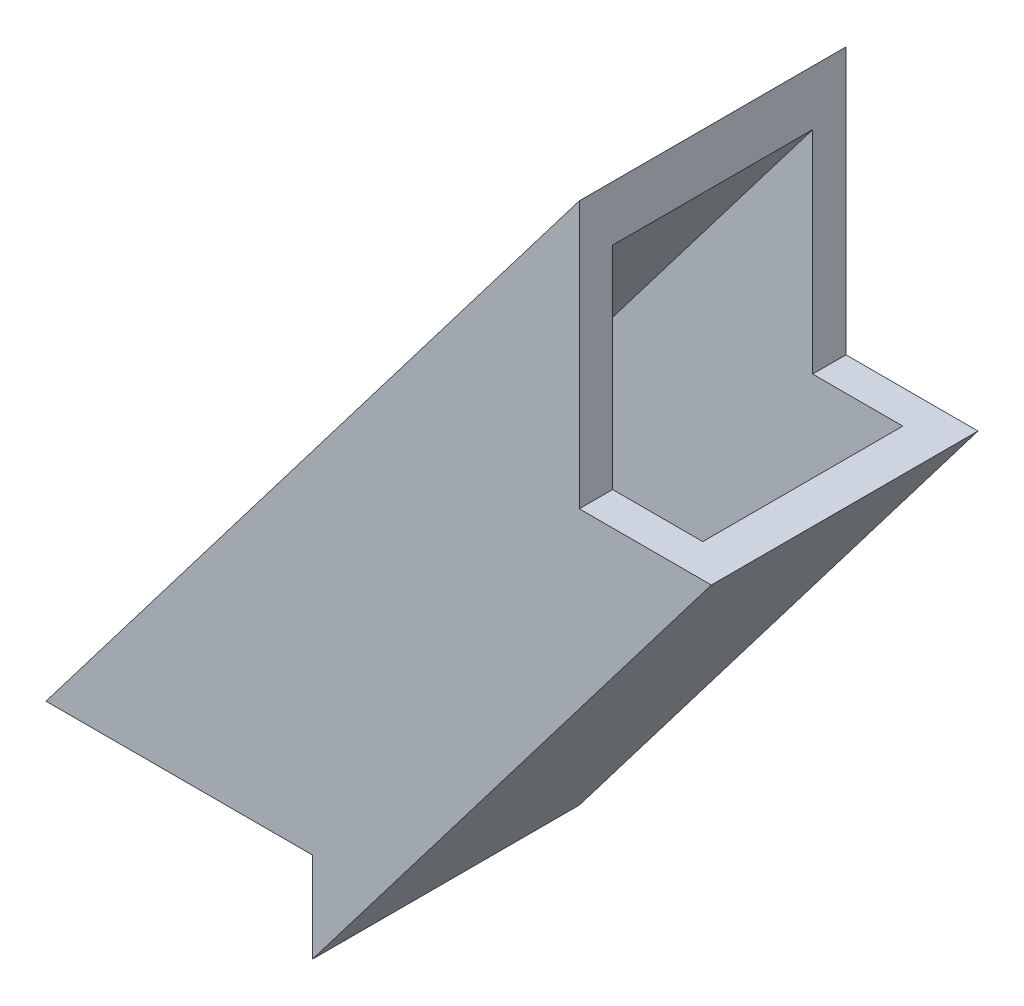
SolidWorks part; units mm, degrees
material "6061-T6 (SS)"
ref_plane "Front Plane" through (0, 0, 0) normal (0, 0, 1) x (1, 0, 0)
ref_plane "Top Plane" through (0, 0, 0) normal (0, 1, 0) x (1, 0, 0)
ref_plane "Right Plane" through (0, 0, 0) normal (1, 0, 0) x (0, 0, -1)
ref_plane "Plane1" through (115.3963, 151.4577, 0) normal (-0.606, -0.7954, 0) x (-0.7954, 0.606, 0)
sketch "Sketch1" plane through (115.3963, 151.4577, 0) normal (-0.606, -0.7954, 0) x (-0.7954, 0.606, 0)
  line L0 (15.3935, -228.6) -> (15.3935, -203.2) construction
  line L1 (-222.1481, -203.2) -> (-196.7481, -203.2)
  line L2 (-222.1481, -203.2) -> (-222.1481, -228.6)
  line L3 (-222.1481, -228.6) -> (-196.7481, -228.6)
  line L4 (-196.7481, -203.2) -> (-196.7481, -228.6)
  line L5 (-222.1481, -203.2) -> (-196.7481, -228.6) construction
  line L6 (-222.1481, -228.6) -> (-196.7481, -203.2) construction
  line L9 (-196.7481, 0) -> (-222.1481, 0) construction
  line L10 (-196.7481, -203.2) -> (-196.7481, 0) construction
  line L11 (-199.9231, -206.375) -> (-199.9231, -225.425)
  line L12 (-218.9731, -225.425) -> (-199.9231, -225.425)
  line L13 (-218.9731, -206.375) -> (-218.9731, -225.425)
  line L14 (-218.9731, -206.375) -> (-199.9231, -206.375)
  point P0 (-209.4481, -215.9)
  point P10 (0, 0)
  point P11 (-187.1344, -241.3)
  dimension "D1" = 3.175
extrude "Boss-Extrude1" add sketch "Sketch1" against normal up to vertex (75.2487 mm away) and the other way up to vertex (8.5737 mm away)
sketch "Sketch2" plane through (0, 0, 0) normal (0, 0, 1) x (1, 0, 0)
  line L0 (342.9, 92.075) -> (317.5, 92.075) construction
  line L1 (317.5, 92.075) -> (317.5, 66.675) construction
  line L2 (342.9, 66.675) -> (317.5, 66.675) construction
  line L3 (342.9, 92.075) -> (342.9, 66.675) construction
  line L4 (292.1, 25.4) -> (266.7, 25.4) construction
  line L5 (266.7, -25.4) -> (266.7, 25.4) construction
  line L6 (292.1, -25.4) -> (266.7, -25.4) construction
  line L7 (292.1, -25.4) -> (292.1, 25.4) construction
  line L8 (342.9, 92.075) -> (317.5, 92.075)
  line L9 (317.5, 92.075) -> (317.5, 66.675)
  line L10 (342.9, 66.675) -> (317.5, 66.675)
  line L11 (342.9, 92.075) -> (342.9, 66.675)
  line L12 (292.1, 25.4) -> (266.7, 25.4)
  line L13 (266.7, -25.4) -> (266.7, 25.4)
  line L14 (292.1, -25.4) -> (266.7, -25.4)
  line L15 (292.1, -25.4) -> (292.1, 25.4)
extrude "Cut-Extrude1" cut sketch "Sketch2" along normal through all
